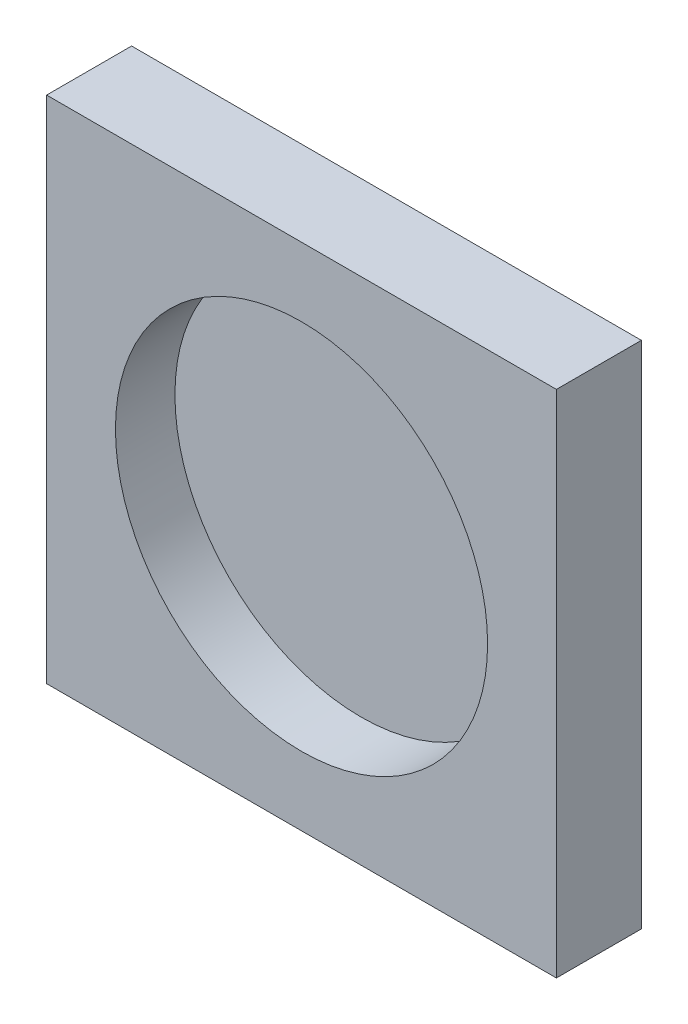
SolidWorks part; units mm, degrees
ref_plane "Front Plane" through (0, 0, 0) normal (0, 0, 1) x (1, 0, 0)
ref_plane "Top Plane" through (0, 0, 0) normal (0, 1, 0) x (1, 0, 0)
ref_plane "Right Plane" through (0, 0, 0) normal (1, 0, 0) x (0, 0, -1)
sketch "Sketch1" plane through (0, 0, 0) normal (0, 0, 1) x (1, 0, 0)
  line L1 (-30, 30) -> (30, 30)
  line L2 (-30, 30) -> (-30, -30)
  line L3 (-30, -30) -> (30, -30)
  line L4 (30, 30) -> (30, -30)
  line L5 (-30, 30) -> (30, -30) construction
  line L6 (-30, -30) -> (30, 30) construction
  point P0 (0, 0)
  dimension "D1" = 60
  dimension "D2" = 60
extrude "Boss-Extrude1" add sketch "Sketch1" along normal blind 10
sketch "Sketch2" plane through (0, 0, 10) normal (0, 0, 1) x (1, 0, 0)
  circle A0 centre (0, 0) radius 21.9
  dimension "D1" = 43.8
extrude "Cut-Extrude1" cut sketch "Sketch2" against normal blind 7
